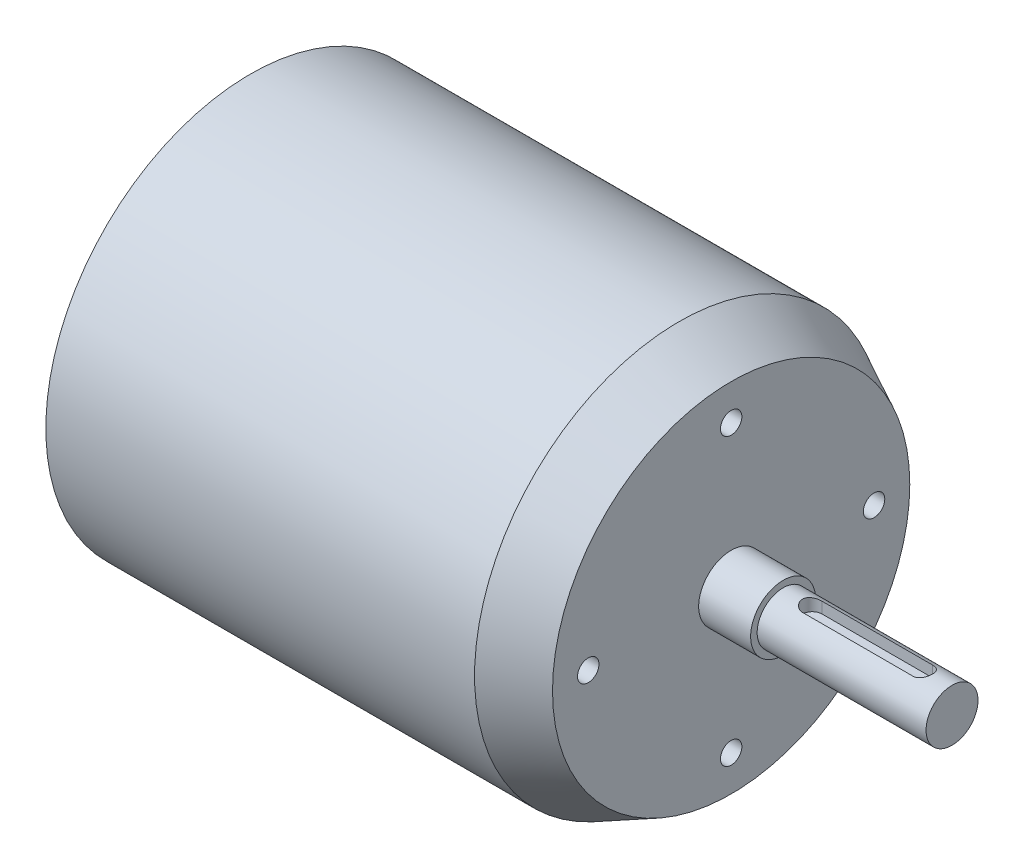
SolidWorks part; units mm, degrees
ref_plane "Front" through (0, 0, 0) normal (0, 0, 1) x (1, 0, 0)
ref_plane "Top" through (0, 0, 0) normal (0, 1, 0) x (1, 0, 0)
ref_plane "Right" through (0, 0, 0) normal (1, 0, 0) x (0, 0, -1)
sketch "草图1" plane through (0, 0, 0) normal (1, 0, 0) x (0, 0, -1)
  circle A0 centre (0, 0) radius 31.5
extrude "凸台-拉伸1" add sketch "草图1" against normal blind 74
sketch "草图2" plane through (0, 0, 0) normal (1, 0, 0) x (0, 0, -1)
  circle A0 centre (0, 0) radius 5
extrude "凸台-拉伸2" add sketch "草图2" along normal blind 8
sketch "草图3" plane through (8, 0, 0) normal (1, 0, 0) x (0, 0, -1)
  circle A0 centre (0, 0) radius 4
extrude "凸台-拉伸3" add sketch "草图3" along normal blind 26
sketch3d "3D草图1"
  line L0 (34, 4, 0) -> (31, 4, 0) construction
  line L1 (31, 4, 0) -> (29.5, 4, 0) construction
  line L2 (8, 4, 0) -> (11, 4, 0) construction
  line L3 (11, 4, 0) -> (12.5, 4, 0) construction
  line L4 (12.5, 4, 1.5) -> (29.5, 4, 1.5)
  line L5 (12.5, 4, -1.5) -> (29.5, 4, -1.5)
  circle A0 centre (34, 0, 0) radius 4 construction
  arc A1 (29.5, 4, 1.5) -> (29.5, 4, -1.5) centre (29.5, 4, 0) ccw
  circle A2 centre (8, 0, 0) radius 4 construction
  arc A3 (12.5, 4, -1.5) -> (12.5, 4, 1.5) centre (12.5, 4, 0) ccw
  point P4 (38, 0, 0)
  point P7 (29.5, 5.5, 0)
  point P12 (12, 0, 0)
  point P15 (12.5, 5.5, 0)
  dimension "D1" = 4
extrude "切除-拉伸1" cut sketch "3D草图1" along direction (0, 1, 0) on the side of the normal blind 2
sketch "草图5" plane through (0, 0, 0) normal (1, 0, 0) x (0, 0, -1)
  circle A0 centre (0, 0) radius 22 construction
  circle A1 centre (0, 22) radius 2 construction
  circle A2 centre (-22, 0) radius 2 construction
  circle A3 centre (0, -22) radius 2 construction
  circle A4 centre (22, 0) radius 2 construction
hole_wizard "M4x0.7 螺纹孔1" positions "3D草图3" profile "草图7" tap size "M4x0.7" standard "ANSI Metric"
sketch3d "3D草图3"
  point P0 (0, 22, 0)
  point P3 (0, 0, -22)
  point P6 (0, -22, 0)
  point P9 (0, 0, 22)
sketch "草图7" plane through (0, 22, 0) normal (0, 1, 0) x (0, 0, -1)
  line L0 (0, 0) -> (0, 6.0914)
  line L1 (0, 6.0914) -> (1.65, 5.1)
  line L2 (1.65, 5.1) -> (1.65, 0)
  line L5 (1.65, 0) -> (0, 0)
  line L10 (0, 6.0914) -> (-1.65, 5.1) construction
  line L11 (0, -6.35) -> (0, 107.95) construction
  dimension "螺纹孔钻头直径" = 3.3
  dimension "螺纹孔钻头深度" = 5.1
  dimension "导头角度" = 118
cosmetic thread "孔螺蚊线1" parameters "D1"=5.1, "D2"=4
cosmetic thread "孔螺蚊线2" parameters "D1"=5.1, "D2"=4
cosmetic thread "孔螺蚊线3" parameters "D1"=5.1, "D2"=4
cosmetic thread "孔螺蚊线4" parameters "D1"=5.1, "D2"=4
sketch "草图9" plane through (0, 0, 0) normal (0, 0, 1) x (1, 0, 0)
  line L0 (0, 31.5) -> (0, 27.5)
  line L1 (0, -31.5) -> (0, 31.5) construction
  line L2 (0, 31.5) -> (-8, 31.5)
  line L3 (0, 31.5) -> (-74, 31.5) construction
  line L4 (-8, 31.5) -> (0, 27.5)
  line L5 (0, 0) -> (-10, 0) construction
revolve "切除-旋转1" cut sketch "草图9" angle 360 about L5
